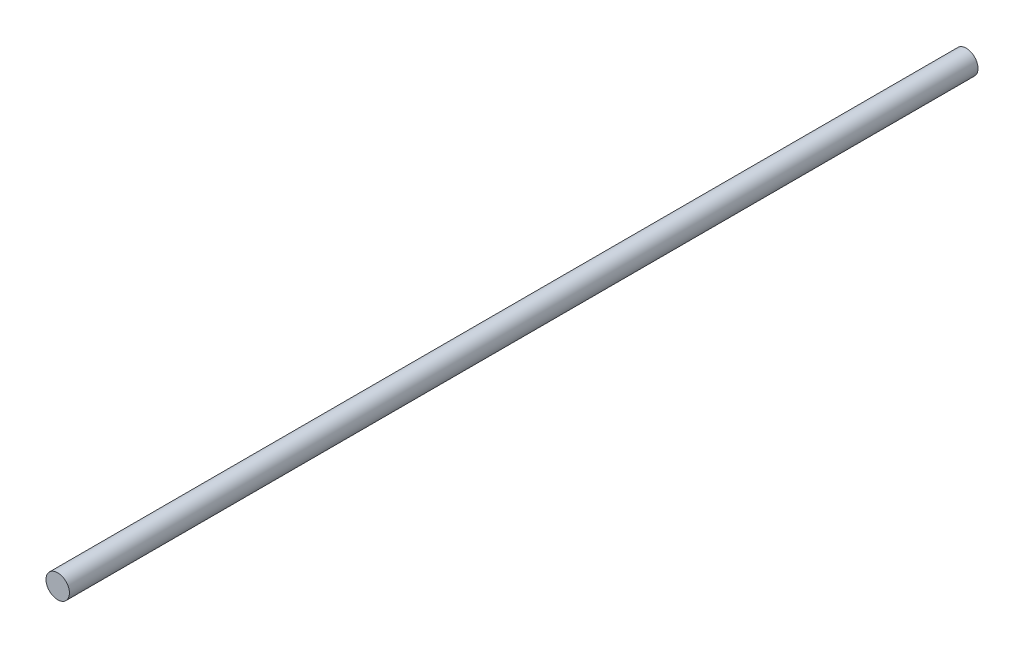
SolidWorks part; units mm, degrees
ref_plane "Alzado" through (0, 0, 0) normal (0, 0, 1) x (1, 0, 0)
ref_plane "Planta" through (0, 0, 0) normal (0, 1, 0) x (1, 0, 0)
ref_plane "Vista lateral" through (0, 0, 0) normal (1, 0, 0) x (0, 0, -1)
sketch "Croquis1" plane through (0, 0, 0) normal (0, 0, 1) x (1, 0, 0)
  circle A0 centre (0, 0) radius 4
  dimension "D1" = 8
extrude "Saliente-Extruir1" add sketch "Croquis1" along normal blind 310
